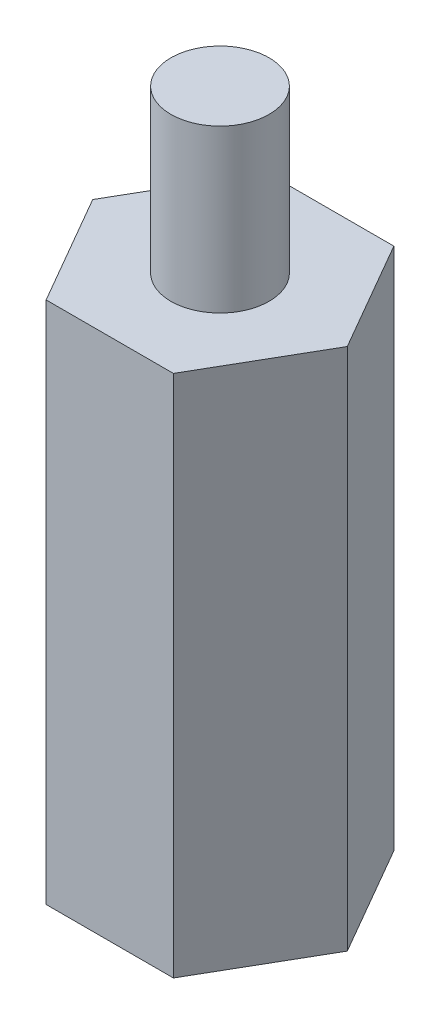
SolidWorks part; units mm, degrees
material "Chrome Stainless Steel"
ref_plane "Front Plane" through (0, 0, 0) normal (0, 0, 1) x (1, 0, 0)
ref_plane "Top Plane" through (0, 0, 0) normal (0, 1, 0) x (1, 0, 0)
ref_plane "Right Plane" through (0, 0, 0) normal (1, 0, 0) x (0, 0, -1)
sketch "Sketch1" plane through (0, 0, 0) normal (0, 1, 0) x (1, 0, 0)
  line L0 (0, 0) -> (3.695, 0) construction
  line L1 (1.8475, 3.2) -> (-1.8475, 3.2)
  line L2 (-1.8475, 3.2) -> (-3.695, 0)
  line L3 (-3.695, 0) -> (-1.8475, -3.2)
  line L4 (-1.8475, -3.2) -> (1.8475, -3.2)
  line L5 (1.8475, -3.2) -> (3.695, 0)
  line L6 (3.695, 0) -> (1.8475, 3.2)
  circle A0 centre (0, 0) radius 3.2 construction
  dimension "D1" = 6.4
extrude "Boss-Extrude1" add sketch "Sketch1" along normal blind 15.2
sketch "Sketch2" plane through (0, 15.2, 0) normal (0, 1, 0) x (1, 0, 0)
  circle A0 centre (0, 0) radius 1.425
  dimension "D1" = 2.85
extrude "Boss-Extrude2" add sketch "Sketch2" along normal blind 4.7
sketch "Sketch3" plane through (0, 0, 0) normal (0, -1, 0) x (1, 0, 0)
  circle A0 centre (0, 0) radius 1.425
  dimension "D1" = 2.85
extrude "Cut-Extrude1" cut sketch "Sketch3" against normal blind 4
